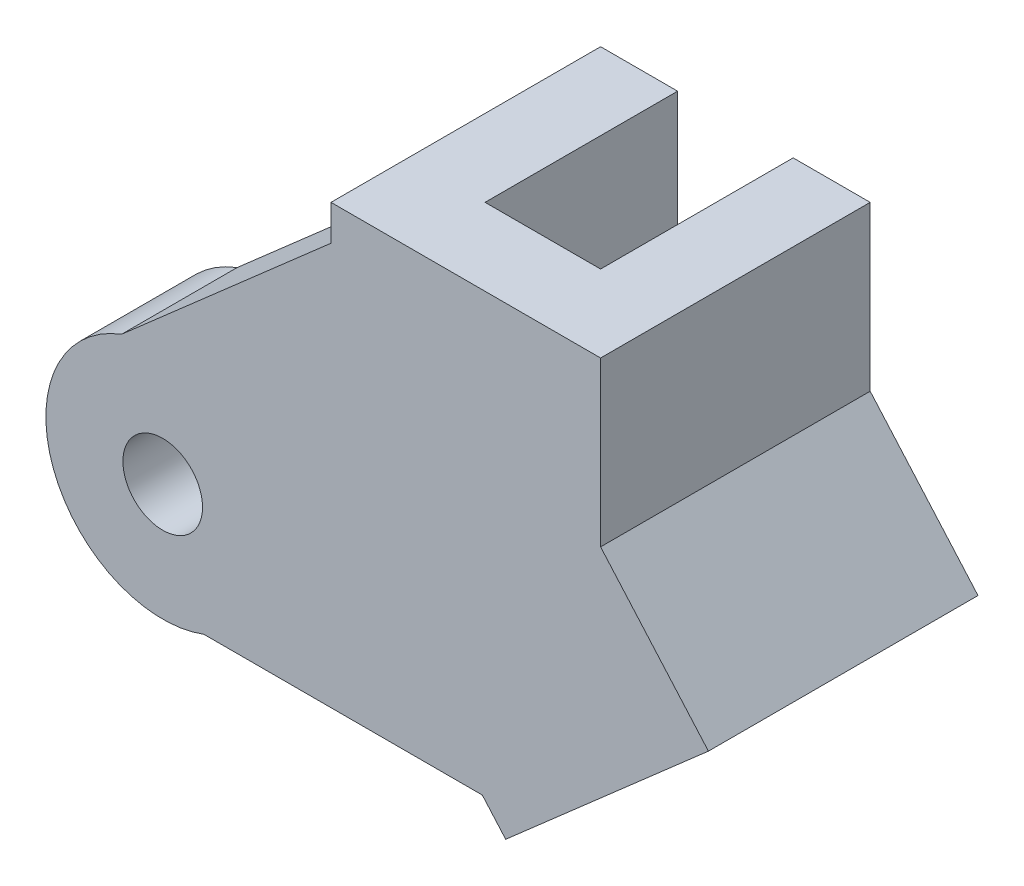
SolidWorks part; units mm, degrees
ref_plane "Front Plane" through (0, 0, 0) normal (0, 0, 1) x (1, 0, 0)
ref_plane "Top Plane" through (0, 0, 0) normal (0, 1, 0) x (1, 0, 0)
ref_plane "Right Plane" through (0, 0, 0) normal (1, 0, 0) x (0, 0, -1)
sketch "Sketch1" plane through (0, 0, 0) normal (0, 0, 1) x (1, 0, 0)
  line L0 (-10.5055, 35.4093) -> (-10.5055, 56.3845) construction
  line L1 (3, 20) -> (-10.5055, 35.4093) construction
  line L2 (-13.5055, 34.2807) -> (-13.5055, 57.6371) construction
  line L3 (0, 18.8714) -> (-13.5055, 34.2807) construction
  line L4 (-10.5055, 35.4093) -> (-10.5055, 56.3845) construction
  line L5 (3, 20) -> (-10.5055, 35.4093) construction
  line L6 (-13.5055, 34.2807) -> (-13.5055, 57.6371) construction
  line L7 (0, 18.8714) -> (-13.5055, 34.2807) construction
  line L8 (-10.5055, 35.4093) -> (-7.2099, 31.6491)
  line L9 (-7.2099, 31.6491) -> (-5.7058, 32.9674)
  line L10 (-5.7058, 32.9674) -> (-8.5055, 36.1617)
  line L11 (-10.5055, 35.4093) -> (-10.5055, 40.4093)
  line L12 (-10.5055, 40.4093) -> (-8.5055, 40.4093)
  line L13 (-8.5055, 40.4093) -> (-8.5055, 36.1617)
  line L14 (-13.5055, 34.2807) -> (-9.466, 29.6718)
  line L15 (-9.466, 29.6718) -> (-10.9701, 28.3535)
  line L16 (-10.9701, 28.3535) -> (-15.5055, 33.5283)
  line L17 (-15.5055, 33.5283) -> (-15.5055, 40.4093)
  line L18 (-15.5055, 40.4093) -> (-13.5055, 40.4093)
  line L19 (-13.5055, 40.4093) -> (-13.5055, 34.2807)
  line L20 (-13.5055, 34.2807) -> (-10.5055, 35.4093) construction
  dimension "D1" = 2
  dimension "D2" = 5
extrude "Boss-Extrude1" add sketch "Sketch1" against normal blind 5 from surface at 0
sketch "Sketch2" plane through (0, 0, 0) normal (0, 0, 1) x (1, 0, 0)
  line L0 (-10.9701, 28.3535) -> (-5.7058, 32.9674)
  line L1 (-8.5055, 36.1617) -> (-5.7058, 32.9674) construction
  line L2 (-5.7058, 32.9674) -> (-8.5055, 36.1617)
  line L3 (-8.5055, 36.1617) -> (-8.5055, 40.4093)
  line L4 (-8.5055, 40.4093) -> (-15.5055, 40.4093)
  line L5 (-15.5055, 40.4093) -> (-15.5055, 33.5283)
  line L6 (-15.5055, 33.5283) -> (-10.9701, 28.3535)
extrude "Boss-Extrude2" add sketch "Sketch2" along normal blind 2
sketch "Sketch3" plane through (0, 0, 2) normal (0, 0, 1) x (1, 0, 0)
  line L0 (-15.5055, 33.5283) -> (-15.5055, 40.4093) construction
  line L1 (-10.9701, 28.3535) -> (-15.5055, 33.5283) construction
  line L3 (-15.5055, 33.5283) -> (-15.5055, 40.4093)
  line L4 (-10.9701, 28.3535) -> (-15.5055, 33.5283)
  line L5 (-20.9434, 34.724) -> (-18.8069, 29.0448) construction
  line L6 (-8.5055, 40.4093) -> (-8.5055, 36.1617) construction
  line L7 (-5.7058, 32.9674) -> (-8.5055, 36.1617) construction
  line L8 (-8.5055, 40.4093) -> (-8.5055, 36.1617)
  line L9 (-5.7058, 32.9674) -> (-8.5055, 36.1617)
  line L10 (-23.5132, 30.5157) -> (0.188, 39.4323) construction
  line L11 (-18.8069, 29.0448) -> (-11.576, 29.0448)
  line L12 (-20.9434, 34.724) -> (-15.5055, 39.49)
  line L13 (-15.5055, 33.5283) -> (-10.9701, 28.3535) construction
  circle A0 centre (-19.8752, 31.8844) radius 1.0339
  arc A1 (-20.9434, 34.724) -> (-18.8069, 29.0448) centre (-19.8752, 31.8844) ccw
  point P13 (-22.7147, 30.8161)
  line M8 (-15.5055, 33.5283) -> (-10.9701, 28.3535)
  dimension "D1" = 2
extrude "Boss-Extrude3" add sketch "Sketch3" against normal blind 3 contours L12 A1 L11 L3 A0 M8
